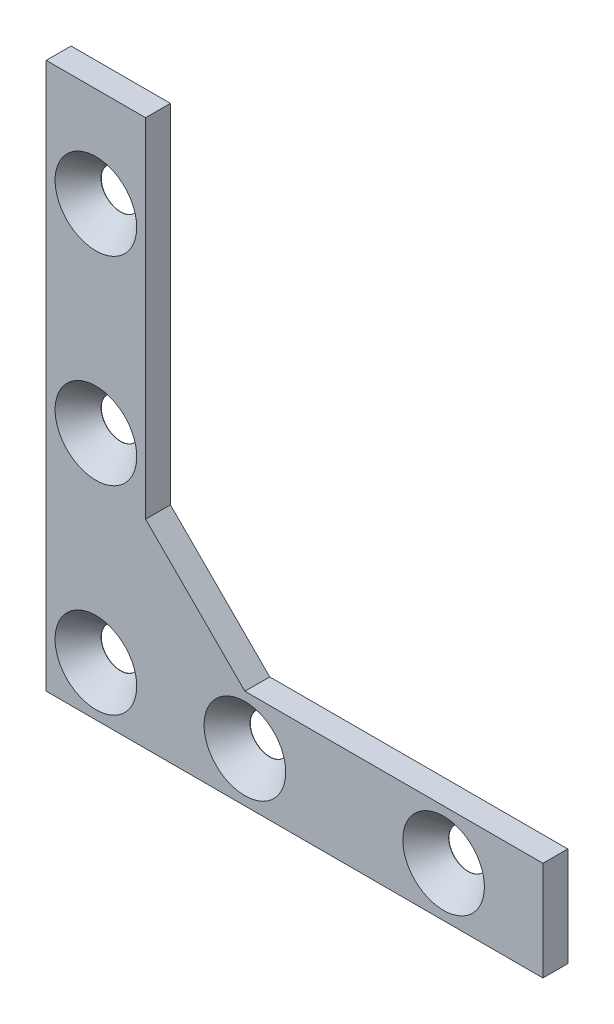
SolidWorks part; units mm, degrees
material "6061 Alloy"
ref_plane "Front Plane" through (0, 0, 0) normal (0, 0, 1) x (1, 0, 0)
ref_plane "Top Plane" through (0, 0, 0) normal (0, 1, 0) x (1, 0, 0)
ref_plane "Right Plane" through (0, 0, 0) normal (1, 0, 0) x (0, 0, -1)
sketch "Sketch1" plane through (0, 0, 0) normal (0, 0, 1) x (1, 0, 0)
  line L1 (-273.4534, -6.35) -> (-273.4534, 63.5)
  line L2 (-273.4534, 63.5) -> (-260.7534, 63.5)
  line L3 (-273.4534, -6.35) -> (-209.9534, -6.35)
  line L10 (-260.7534, 19.05) -> (-260.7534, 63.5)
  line L11 (-209.9534, -6.35) -> (-209.9534, 6.35)
  line L12 (-209.9534, 6.35) -> (-248.0534, 6.35)
  line L13 (-248.0534, 6.35) -> (-260.7534, 19.05)
  dimension "D1" = 69.85
  dimension "D2" = 63.5
  dimension "D3" = 12.7
  dimension "D4" = 38.1
  dimension "D5" = 12.7
  dimension "D6" = 44.45
extrude "Boss-Extrude1" add sketch "Sketch1" along normal blind 3.175
sketch "Sketch2" plane through (0, 0, 3.175) normal (0, 0, 1) x (1, 0, 0)
  line L0 (-267.1034, 63.5) -> (-267.1034, 50.8) construction
  line L1 (-260.7534, 63.5) -> (-273.4534, 63.5) construction
  line L2 (-267.1034, 50.8) -> (-267.1034, 25.4) construction
  line L3 (-267.1034, 0) -> (-248.0534, 0) construction
  line L4 (-267.1034, 25.4) -> (-267.1034, 0) construction
  line L5 (-248.0534, 0) -> (-222.6534, 0) construction
  line L6 (-209.7517, 0) -> (-222.6534, 0) construction
  line L7 (-273.4534, -6.35) -> (-209.9534, -6.35) construction
  point P9 (0, 0)
  dimension "D1" = 25.4
  dimension "D2" = 19.05
  dimension "D3" = 25.4
  dimension "D4" = 6.35
hole_wizard "#10 Clearance Hole1" positions "Sketch3" profile "Sketch4" hole size "#10" standard "ANSI Inch" end condition through all
sketch "Sketch3" plane through (0, 0, 3.175) normal (0, 0, 1) x (1, 0, 0)
  point P0 (-267.1034, 0)
  point P3 (-267.1034, 25.4)
  point P6 (-267.1034, 50.8)
  point P9 (-248.0534, 0)
  point P12 (-222.6534, 0)
sketch "Sketch4" plane through (-267.1034, 0, 3.175) normal (1, 0, 0) x (0, -1, 0)
  line L0 (0, 0) -> (0, 3.175)
  line L1 (0, 3.175) -> (2.4892, 3.175)
  line L2 (2.4892, 3.175) -> (2.4892, 3.1411)
  line L3 (2.4892, 3.1411) -> (5.2197, 0)
  line L5 (5.2197, 0) -> (0, 0)
  line L6 (-2.4892, 3.1411) -> (-5.2197, 0) construction
  line L11 (0, -6.35) -> (0, 107.95) construction
  dimension "Thru Hole Dia." = 4.9784
  dimension "Thru Hole Depth" = 3.175
  dimension "Near C'Sink Dia." = 10.4394
  dimension "Near C'Sink Angle" = 82
